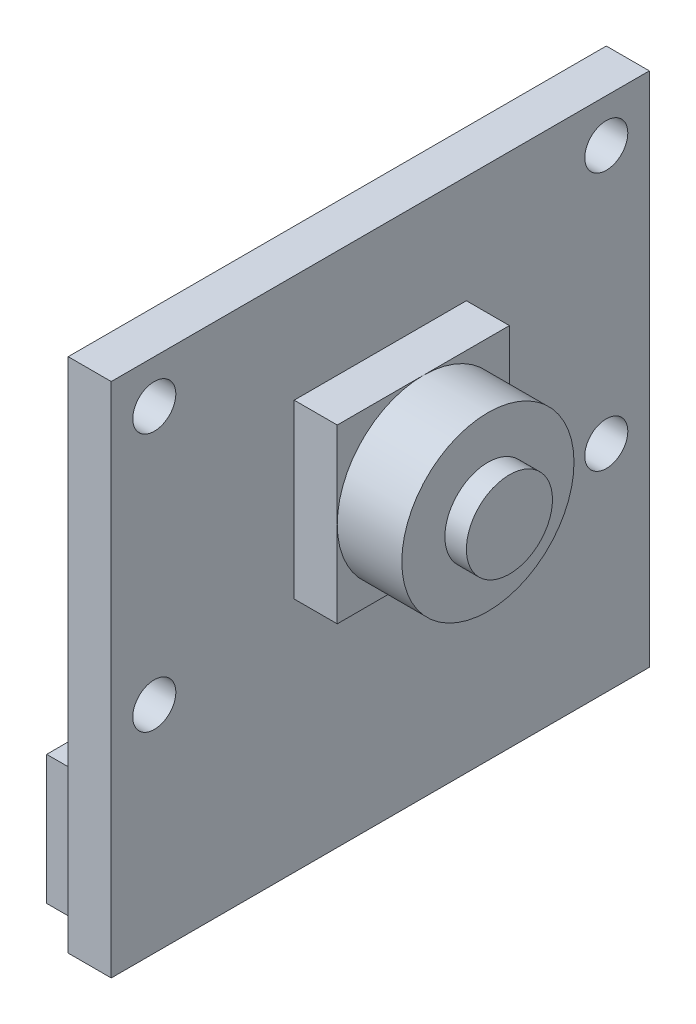
SolidWorks part; units mm, degrees
ref_plane "Front Plane" through (0, 0, 0) normal (0, 0, 1) x (1, 0, 0)
ref_plane "Top Plane" through (0, 0, 0) normal (0, 1, 0) x (1, 0, 0)
ref_plane "Right Plane" through (0, 0, 0) normal (1, 0, 0) x (0, 0, -1)
sketch "Sketch1" plane through (0, 0, 0) normal (1, 0, 0) x (0, 0, -1)
  line L0 (0, -32.0876) -> (0, 32.0876) construction
  line L1 (-12.5, -12) -> (12.5, -12)
  line L2 (-12.5, -12) -> (-12.5, 12)
  line L3 (-12.5, 12) -> (12.5, 12)
  line L4 (12.5, -12) -> (12.5, 12)
  line L5 (-12.5, -12) -> (12.5, 12) construction
  line L6 (-12.5, 12) -> (12.5, -12) construction
  circle A0 centre (10.5, 10) radius 1
  circle A2 centre (10.5, -2) radius 1
  circle A3 centre (-10.5, 10) radius 1
  circle A4 centre (-10.5, -2) radius 1
  point P0 (0, 0)
  point P10 (11.5, 10)
  point P13 (0, 0)
  point P14 (10.5, 11)
  point P16 (10.5, -1)
  dimension "D3" = 2
  dimension "D6" = 2
  dimension "D7" = 2
  dimension "D8" = 21
  dimension "D9" = 12
  dimension "D1" = 25
  dimension "D2" = 24
  dimension "D4" = 1
  dimension "D5" = 14
extrude "Boss-Extrude1" add sketch "Sketch1" along normal blind 2
sketch "Sketch2" plane through (2, 0, 0) normal (1, 0, 0) x (0, 0, -1)
  line L0 (12.5, 12) -> (-12.5, 12) construction
  line L1 (-4, 7) -> (4, 7)
  line L2 (-4, 7) -> (-4, -1)
  line L3 (-4, -1) -> (4, -1)
  line L4 (4, 7) -> (4, -1)
  line L5 (-4, 7) -> (4, -1) construction
  line L6 (-4, -1) -> (4, 7) construction
  line L7 (12.5, -12) -> (12.5, 12) construction
  point P0 (0, 3)
  point P9 (0, 7)
  dimension "D1" = 8
  dimension "D2" = 8
  dimension "D3" = 13
extrude "Boss-Extrude2" add sketch "Sketch2" along normal blind 2
sketch "Sketch3" plane through (4, 0, 0) normal (1, 0, 0) x (0, 0, -1)
  line L0 (4, 7) -> (-4, 7) construction
  line L1 (4, -1) -> (4, 7) construction
  line L2 (-12.5, 12) -> (-12.5, -12) construction
  circle A0 centre (0, 3) radius 4
  dimension "D1" = 8
extrude "Boss-Extrude3" add sketch "Sketch3" along normal blind 3
sketch "Sketch4" plane through (7, 0, 0) normal (1, 0, 0) x (0, 0, -1)
  circle A0 centre (0, 3) radius 2
  dimension "D1" = 4
extrude "Boss-Extrude4" add sketch "Sketch4" along normal blind 1
sketch "Sketch5" plane through (0, 0, 0) normal (-1, 0, 0) x (0, 0, 1)
  line L1 (-10.5, -6.5) -> (10.5, -6.5)
  line L2 (-10.5, -6.5) -> (-10.5, -12.5)
  line L3 (-10.5, -12.5) -> (10.5, -12.5)
  line L4 (10.5, -6.5) -> (10.5, -12.5)
  line L5 (-12.5, -12) -> (-12.5, 12) construction
  line L6 (12.5, 12) -> (12.5, -12) construction
  line L7 (12.5, -12) -> (-12.5, -12) construction
  dimension "D1" = 6
  dimension "D2" = 2
  dimension "D3" = 2
  dimension "D4" = 0.5
extrude "Boss-Extrude5" add sketch "Sketch5" along normal blind 3
